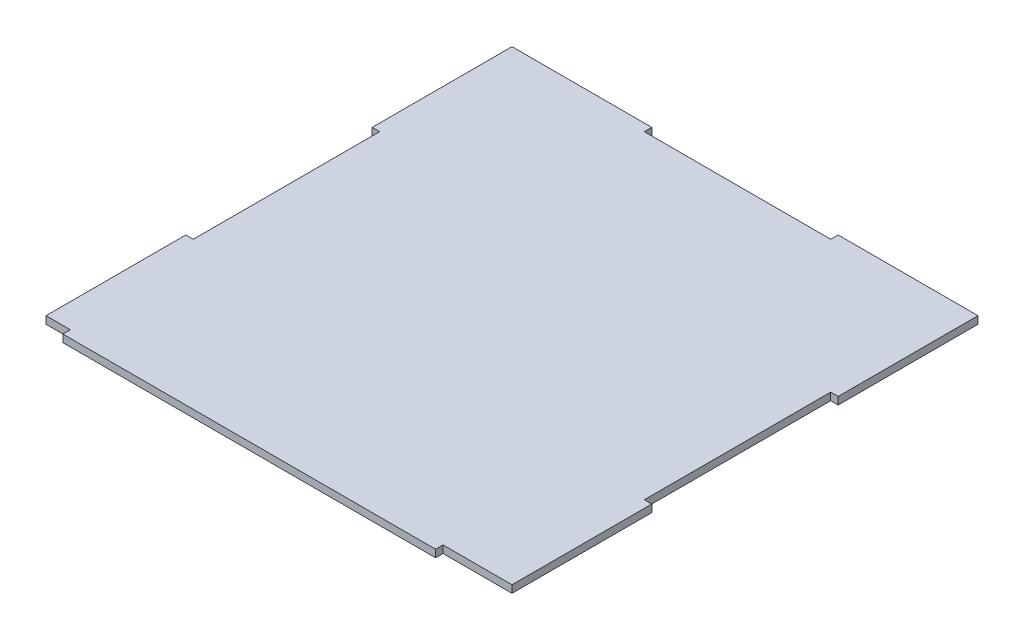
SolidWorks part; units mm, degrees
ref_plane "Front Plane" through (0, 0, 0) normal (0, 0, 1) x (1, 0, 0)
ref_plane "Top Plane" through (0, 0, 0) normal (0, 1, 0) x (1, 0, 0)
ref_plane "Right Plane" through (0, 0, 0) normal (1, 0, 0) x (0, 0, -1)
sketch "Sketch1" plane through (0, 0, 0) normal (0, 1, 0) x (1, 0, 0)
  line L0 (-125, 2.3524) -> (-112, 2.3524)
  line L1 (-112, 2.3524) -> (-112, -1.6476)
  line L2 (-112, -1.6476) -> (88, -1.6476)
  line L3 (88, -1.6476) -> (88, 2.3524)
  line L4 (88, 2.3524) -> (125, 2.3524)
  line L5 (-125, 2.3524) -> (-125, 77.3524)
  line L6 (-125, 77.3524) -> (-121, 77.3524)
  line L7 (-121, 77.3524) -> (-121, 177.3524)
  line L8 (-121, 177.3524) -> (-125, 177.3524)
  line L9 (-125, 177.3524) -> (-125, 252.3524)
  line L10 (-125, 252.3524) -> (-50, 252.3524)
  line L12 (-50, 252.3524) -> (-50, 248.3524)
  line L13 (-50, 248.3524) -> (50, 248.3524)
  line L14 (50, 248.3524) -> (50, 252.3524)
  line L15 (50, 252.3524) -> (125, 252.3524)
  line L16 (125, 252.3524) -> (125, 177.3524)
  line L17 (125, 177.3524) -> (121, 177.3524)
  line L18 (121, 177.3524) -> (121, 77.3524)
  line L19 (121, 77.3524) -> (125, 77.3524)
  line L20 (125, 77.3524) -> (125, 2.3524)
  dimension "D1" = 13
  dimension "D2" = 200
  dimension "D3" = 250
  dimension "D4" = 75
  dimension "D5" = 100
  dimension "D6" = 75
  dimension "D7" = 75
  dimension "D8" = 250
extrude "Boss-Extrude3" add sketch "Sketch1" along normal blind 4 contours L9 L10 L12 L13 L14 L15 L16 L17 L18 L19 L20 L4 L3 L2 L1 L0 L5 L6 L7 L8
